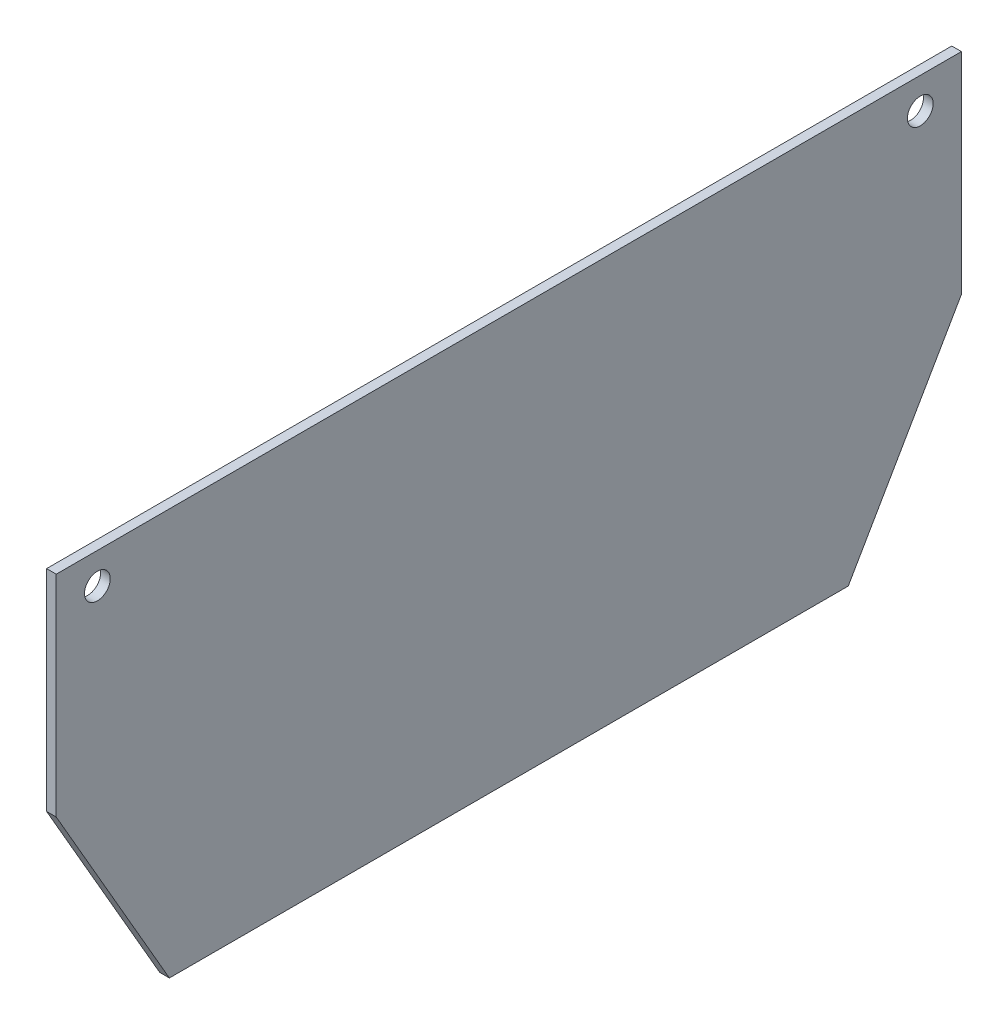
SolidWorks part; units mm, degrees
material "Pine"
ref_plane "Front Plane" through (0, 0, 0) normal (0, 0, 1) x (1, 0, 0)
ref_plane "Top Plane" through (0, 0, 0) normal (0, 1, 0) x (1, 0, 0)
ref_plane "Right Plane" through (0, 0, 0) normal (1, 0, 0) x (0, 0, -1)
sketch "Sketch1" plane through (0, 0, 0) normal (1, 0, 0) x (0, 0, -1)
  line L1 (-558.8, -250.825) -> (558.8, -250.825)
  line L2 (-558.8, -250.825) -> (-558.8, 250.825)
  line L3 (-558.8, 250.825) -> (558.8, 250.825)
  line L4 (558.8, -250.825) -> (558.8, 250.825)
  line L5 (-558.8, -250.825) -> (558.8, 250.825) construction
  line L6 (-558.8, 250.825) -> (558.8, -250.825) construction
  point P0 (0, 0)
  dimension "D1" = 1117.6
  dimension "D2" = 501.65
extrude "Boss-Extrude1" add sketch "Sketch1" along normal blind 11.9062
sketch "Sketch3" plane through (11.9062, 0, 0) normal (1, 0, 0) x (0, 0, -1)
  line L1 (558.8, 250.825) -> (-558.8, 250.825) construction
  circle A0 centre (-508, 212.725) radius 15.875
  circle A1 centre (508, 212.725) radius 15.875
  dimension "D3" = 31.75
  dimension "D1" = 508
  dimension "D2" = 508
  dimension "D4" = 38.1
extrude "Cut-Extrude1" cut sketch "Sketch3" against normal through all
chamfer "Chamfer1" distance 139.7 angle 60 2 edges at (5.9531, -250.825, -558.8) (5.9531, -250.825, 558.8)
